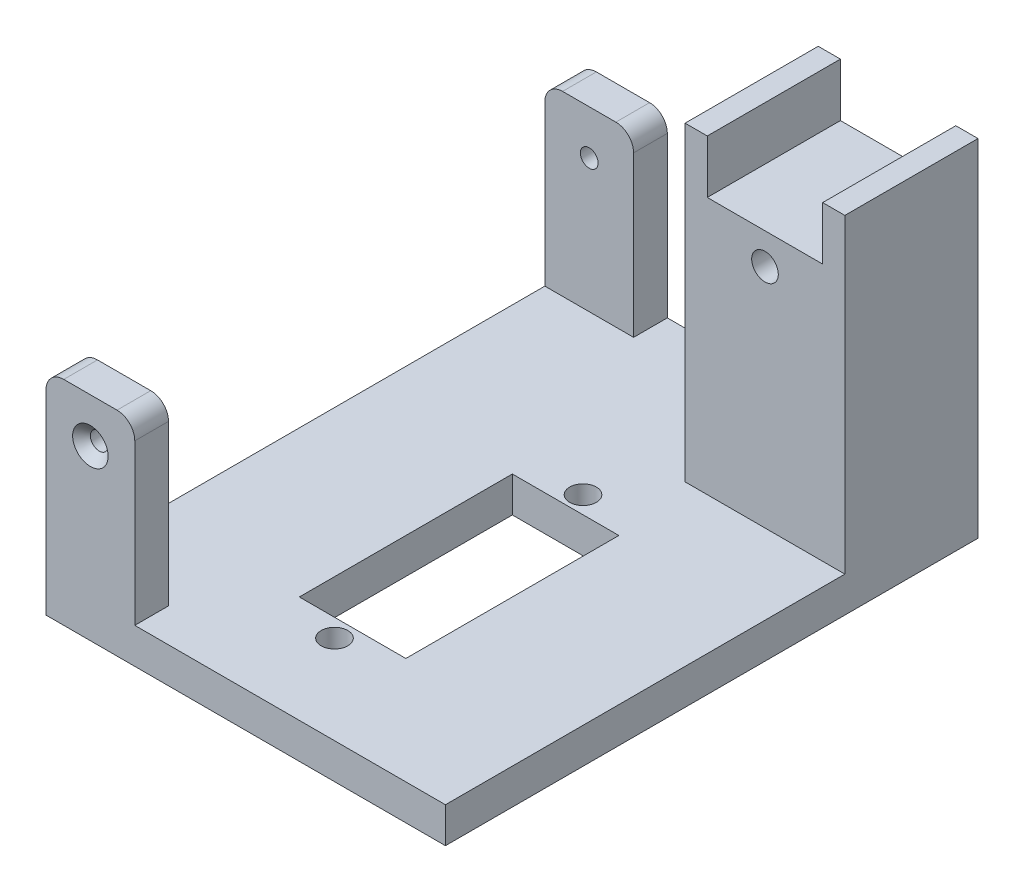
SolidWorks part; units mm, degrees
ref_plane "Front Plane" through (0, 0, 0) normal (0, 0, 1) x (1, 0, 0)
ref_plane "Top Plane" through (0, 0, 0) normal (0, 1, 0) x (1, 0, 0)
ref_plane "Right Plane" through (0, 0, 0) normal (1, 0, 0) x (0, 0, -1)
sketch "Sketch1" plane through (0, 0, 0) normal (0, 1, 0) x (1, 0, 0)
  line L1 (-22.5, 30) -> (22.5, 30)
  line L2 (-22.5, 30) -> (-22.5, -30)
  line L3 (-22.5, -30) -> (22.5, -30)
  line L4 (22.5, 30) -> (22.5, -30)
  line L5 (-22.5, 30) -> (22.5, -30) construction
  line L6 (-22.5, -30) -> (22.5, 30) construction
  point P0 (0, 0)
  dimension "D1" = 45
  dimension "D2" = 60
extrude "Boss-Extrude1" add sketch "Sketch1" along normal blind 4
sketch "Sketch2" plane through (0, 4, 0) normal (0, 1, 0) x (1, 0, 0)
  line L1 (-22.5, 30) -> (-12.5, 30)
  line L2 (-22.5, 30) -> (-22.5, 26.2)
  line L3 (-22.5, 26.2) -> (-12.5, 26.2)
  line L4 (-12.5, 30) -> (-12.5, 26.2)
  line L5 (-22.5, 30) -> (-12.5, 26.2) construction
  line L6 (-22.5, 26.2) -> (-12.5, 30) construction
  line L7 (-22.5, -26.2) -> (-12.5, -26.2)
  line L8 (-22.5, -26.2) -> (-22.5, -30)
  line L9 (-22.5, -30) -> (-12.5, -30)
  line L10 (-12.5, -26.2) -> (-12.5, -30)
  line L11 (-22.5, -26.2) -> (-12.5, -30) construction
  line L12 (-22.5, -30) -> (-12.5, -26.2) construction
  line L13 (22.5, 30) -> (-22.5, 30) construction
  line L14 (-22.5, 30) -> (-22.5, -30) construction
  line L15 (-22.5, -30) -> (22.5, -30) construction
  point P0 (-17.5, 28.1)
  point P5 (-17.5, -28.1)
  dimension "D1" = 3.8
  dimension "D2" = 3.8
  dimension "D3" = 10
  dimension "D4" = 10
  dimension "D9" = 52.4
extrude "Boss-Extrude2" add sketch "Sketch2" along normal blind 20
sketch "Sketch3" plane through (0, 0, 30) normal (0, 0, 1) x (1, 0, 0)
  line L0 (-22.5, 24) -> (-12.5, 24) construction
  line L3 (-22.5, 24) -> (-12.5, 24) construction
  circle A0 centre (-17.5, 19) radius 1
  point P7 (-17.5, 24)
  dimension "D1" = 2
  dimension "D2" = 5
extrude "Cut-Extrude1" cut sketch "Sketch3" against normal up to next contours A0
sketch "Sketch4" plane through (0, 0, -30) normal (0, 0, -1) x (-1, 0, 0)
  line L0 (12.5, 24) -> (22.5, 24) construction
  line L2 (12.5, 24) -> (22.5, 24) construction
  circle A0 centre (17.5, 19) radius 1
  point P6 (17.5, 24)
  dimension "D1" = 2
  dimension "D2" = 5
extrude "Cut-Extrude2" cut sketch "Sketch4" against normal up to next
sketch "Sketch5" plane through (0, 4, 0) normal (0, 1, 0) x (1, 0, 0)
  line L0 (22.5, -30) -> (22.5, 30) construction
  line L1 (4.5, 30) -> (22.5, 30)
  line L2 (4.5, 30) -> (4.5, 15)
  line L3 (4.5, 15) -> (22.5, 15)
  line L4 (22.5, 30) -> (22.5, 15)
  line L5 (4.5, 30) -> (22.5, 15) construction
  line L6 (4.5, 15) -> (22.5, 30) construction
  line L8 (-12.5, 26.2) -> (-12.5, 30) construction
  line L9 (22.5, 30) -> (-12.5, 30) construction
  point P0 (13.5, 22.5)
  dimension "D1" = 15
  dimension "D2" = 18
  dimension "D4" = 17
extrude "Boss-Extrude3" add sketch "Sketch5" along normal blind 35
sketch "Sketch6" plane through (0, 39, 0) normal (0, 1, 0) x (1, 0, 0)
  line L0 (22.5, 30) -> (4.5, 30) construction
  line L1 (7, 30) -> (20, 30)
  line L2 (7, 30) -> (7, 10)
  line L3 (7, 10) -> (20, 10)
  line L4 (20, 30) -> (20, 10)
  line L5 (7, 30) -> (20, 10) construction
  line L6 (7, 10) -> (20, 30) construction
  line L8 (22.5, 15) -> (22.5, 30) construction
  line L10 (4.5, 30) -> (4.5, 15) construction
  point P0 (13.5, 20)
  point P10 (13.5, 10)
  dimension "D1" = 13
  dimension "D2" = 20
  dimension "D3" = 2.5
  dimension "D4" = 2.5
extrude "Cut-Extrude3" cut sketch "Sketch6" against normal blind 6
sketch "Sketch7" plane through (0, 0, -30) normal (0, 0, -1) x (-1, 0, 0)
  line L0 (-20, 33) -> (-7, 33) construction
  circle A0 centre (-13.5, 29.5) radius 1.5
  point P4 (-13.5, 33)
  dimension "D1" = 3
  dimension "D2" = 3.5
extrude "Cut-Extrude4" cut sketch "Sketch7" against normal up to next
fillet "Fillet1" radius 2 4 edges at (-12.5, 24, -28.1) (-22.5, 24, -28.1) (-12.5, 24, 28.1) (-22.5, 24, 28.1)
fillet "Chamfer1" [suppressed] radius 5
fillet "Chamfer2" radius 1 1 edges at (-18.5, 19, -30) profile chamfer
fillet "Chamfer3" radius 1 1 edges at (-16.5, 19, 30) profile chamfer
sketch "Sketch8" plane through (0, 0, 0) normal (0, -1, 0) x (1, 0, 0)
  line L0 (22.5, -30) -> (-22.5, -30) construction
  line L1 (-6, 17.9602) -> (6, 17.9602)
  line L2 (-6, 17.9602) -> (-6, -6.0398)
  line L3 (-6, -6.0398) -> (6, -6.0398)
  line L4 (6, 17.9602) -> (6, -6.0398)
  line L5 (22.5, 30) -> (22.5, -30) construction
  circle A1 centre (0, -8) radius 1.5
  circle A2 centre (0, 20) radius 1.5
  circle A3 centre (0, 0) radius 2
  point P2 (0, -6.0398)
  point P12 (0, -30)
  point P16 (22.5, 0)
  dimension "D1" = 12
  dimension "D2" = 3
  dimension "D4" = 3
  dimension "D6" = 4
  dimension "D7" = 8
  dimension "D3" = 24
  dimension "D5" = 28
extrude "Cut-Extrude5" cut sketch "Sketch8" against normal up to next
